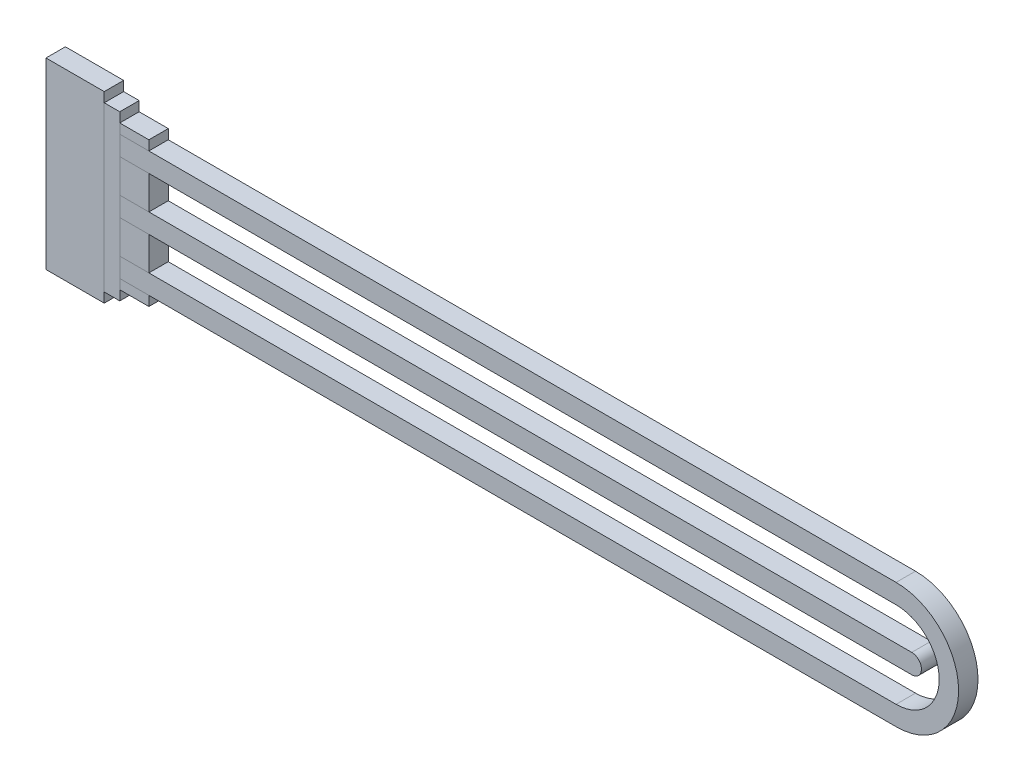
SolidWorks part; units mm, degrees
ref_plane "Alzado" through (0, 0, 0) normal (0, 0, 1) x (1, 0, 0)
ref_plane "Planta" through (0, 0, 0) normal (0, 1, 0) x (1, 0, 0)
ref_plane "Vista lateral" through (0, 0, 0) normal (1, 0, 0) x (0, 0, -1)
sketch "Sketch1" plane through (0, 0, 0) normal (0, 0, 1) x (1, 0, 0)
  line L0 (0, 0) -> (400, 0)
  line L1 (400, -64.4097) -> (0, -64.4097)
  line L2 (0, -10) -> (400, -10)
  line L3 (400, -54.4097) -> (0, -54.4097)
  line L4 (0, -10) -> (0, 0)
  line L5 (0, -54.4097) -> (0, -64.4097)
  line L6 (432.2048, -32.2048) -> (0, -32.2048) construction
  line L7 (0, -27.2048) -> (408.0642, -27.2048)
  line L8 (0, -27.2048) -> (0, -37.2048)
  line L9 (0, -37.2048) -> (408.0642, -37.2048)
  arc A0 (400, 0) -> (400, -64.4097) centre (400, -32.2048) cw
  arc A1 (400, -10) -> (400, -54.4097) centre (400, -32.2048) cw
  arc A4 (408.0642, -27.2048) -> (408.0642, -37.2048) centre (408.0642, -32.2048) cw
  dimension "D1" = 32.2048
  dimension "D3" = 10
  dimension "D2" = 400
  dimension "D4" = 5
extrude "Boss-Extrude1" add sketch "Sketch1" along normal blind 10
sketch "Sketch2" plane through (0, 0, 0) normal (-1, 0, 0) x (0, 0, 1)
  line L0 (5, 0) -> (5, -10) construction
  line L1 (10, 0) -> (0, 0) construction
  line L2 (10, -10) -> (0, -10) construction
  circle A0 centre (5, -4.907) radius 3
  dimension "D1" = 6
extrude "Boss-Extrude2" add sketch "Sketch2" along normal blind 15 separate body
sketch "Sketch3" plane through (0, 0, 0) normal (-1, 0, 0) x (0, 0, 1)
  line L0 (5, -54.4097) -> (5, -64.4097) construction
  line L1 (10, -54.4097) -> (0, -54.4097) construction
  line L2 (10, -64.4097) -> (0, -64.4097) construction
  circle A0 centre (5, -59.4097) radius 3
  dimension "D1" = 6
extrude "Boss-Extrude3" add sketch "Sketch3" along normal blind 15 separate body
sketch "Sketch4" plane through (0, 0, 0) normal (1, 0, 0) x (0, 0, -1)
  line L0 (-5, 0) -> (-5, -64.4097) construction
  line L1 (-10, 0) -> (0, 0) construction
  line L2 (-10, -64.4097) -> (0, -64.4097) construction
  line L3 (-10, -54.4097) -> (-10, -64.4097) construction
  line L4 (0, 5) -> (-10, 5)
  line L5 (0, 5) -> (0, -69.4097)
  line L6 (0, -69.4097) -> (-10, -69.4097)
  line L7 (-10, 5) -> (-10, -69.4097)
  line L8 (0, 5) -> (-10, -69.4097) construction
  line L9 (0, -69.4097) -> (-10, 5) construction
  line L10 (0, -32.2048) -> (-10, -32.2048) construction
  point P6 (-5, -32.2048)
  point P13 (-10, -59.4097)
  dimension "D1" = 5
extrude "Boss-Extrude4" add sketch "Sketch4" along normal blind 15 separate body
sketch "Sketch5" plane through (0, 0, 0) normal (-1, 0, 0) x (0, 0, 1)
  line L0 (5, 5) -> (5, -69.4097) construction
  line L1 (0, 5) -> (10, 5) construction
  line L2 (10, -69.4097) -> (0, -69.4097) construction
  line L3 (0, -32.2048) -> (10, -32.2048) construction
  line L4 (0, 10) -> (10, 10)
  line L5 (0, 10) -> (0, -74.4097)
  line L6 (0, -74.4097) -> (10, -74.4097)
  line L7 (10, 10) -> (10, -74.4097)
  line L8 (0, 10) -> (10, -74.4097) construction
  line L9 (0, -74.4097) -> (10, 10) construction
  line L12 (0, -54.4097) -> (0, -64.4097) construction
  point P6 (5, -32.2048)
  dimension "D1" = 5
extrude "Boss-Extrude5" add sketch "Sketch5" along normal blind 8 separate body
sketch "Sketch6" plane through (-8, 0, 0) normal (-1, 0, 0) x (0, 0, 1)
  line L0 (5, 10) -> (5, -74.4097) construction
  line L1 (10, 10) -> (0, 10) construction
  line L2 (0, -74.4097) -> (10, -74.4097) construction
  line L3 (10, -74.4097) -> (10, 10) construction
  line L4 (0, 15) -> (10, 15)
  line L5 (0, 15) -> (0, -79.4097)
  line L6 (0, -79.4097) -> (10, -79.4097)
  line L7 (10, 15) -> (10, -79.4097)
  line L8 (0, 15) -> (10, -79.4097) construction
  line L9 (0, -79.4097) -> (10, 15) construction
  line L10 (0, -32.2048) -> (10, -32.2048) construction
  point P6 (5, -32.2048)
  dimension "D1" = 5
extrude "Boss-Extrude6" add sketch "Sketch6" along normal blind 30 separate body
